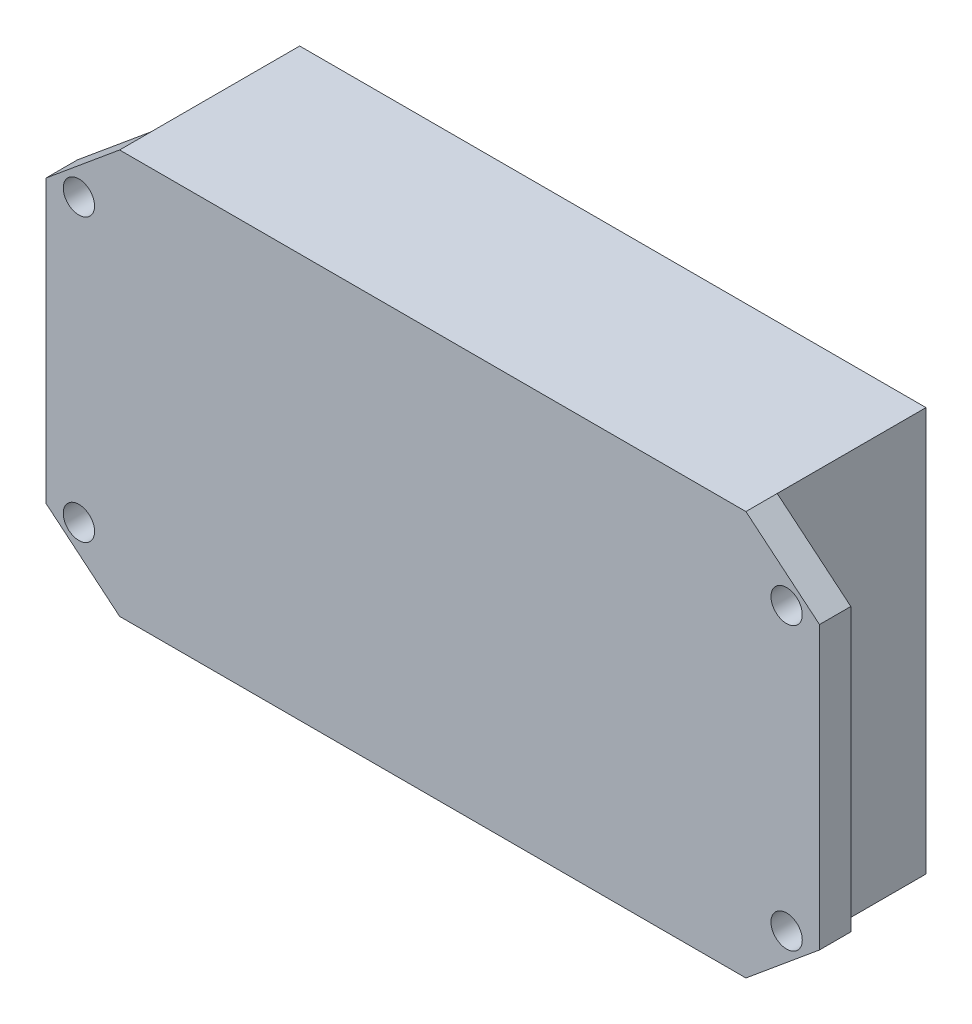
SolidWorks part; units mm, degrees
ref_plane "前视基准面" through (0, 0, 0) normal (0, 0, 1) x (1, 0, 0)
ref_plane "上视基准面" through (0, 0, 0) normal (0, 1, 0) x (1, 0, 0)
ref_plane "右视基准面" through (0, 0, 0) normal (1, 0, 0) x (0, 0, -1)
sketch "草图1" plane through (0, 0, 0) normal (0, 0, 1) x (1, 0, 0)
  line L1 (-20, 12.9) -> (20, 12.9)
  line L2 (-20, 12.9) -> (-20, -12.9)
  line L3 (-20, -12.9) -> (20, -12.9)
  line L4 (20, 12.9) -> (20, -12.9)
  line L5 (-20, 12.9) -> (20, -12.9) construction
  line L6 (-20, -12.9) -> (20, 12.9) construction
  point P0 (0, 0)
  dimension "D1" = 40
  dimension "D2" = 25.8
extrude "凸台-拉伸1" add sketch "草图1" along normal blind 9.5
sketch "草图2" plane through (0, 0, 9.5) normal (0, 0, 1) x (1, 0, 0)
  line L0 (0, -5.225) -> (0, 5.225) construction
  line L1 (-20, 12.9) -> (20, 12.9)
  line L2 (-24.7, 9) -> (-24.7, -9)
  line L3 (-20, -12.9) -> (20, -12.9)
  line L4 (24.7, 9) -> (24.7, -9)
  line L5 (-21.8155, 11.3935) -> (21.8155, -11.3935) construction
  line L6 (-21.8155, -11.3935) -> (21.8155, 11.3935) construction
  line L8 (5.225, 0) -> (-5.225, 0) construction
  line L9 (-20, 12.9) -> (-24.7, 9)
  line L10 (20, 12.9) -> (24.7, 9)
  line L11 (20, -12.9) -> (24.7, -9)
  line L12 (-20, -12.9) -> (-24.7, -9)
  circle A0 centre (-22.6, 9) radius 1
  circle A1 centre (22.6, 9) radius 1
  circle A2 centre (22.6, -9) radius 1
  circle A3 centre (-22.6, -9) radius 1
  point P0 (0, 0)
  dimension "D3" = 22.6
  dimension "D4" = 9
extrude "凸台-拉伸2" add sketch "草图2" along normal blind 2
